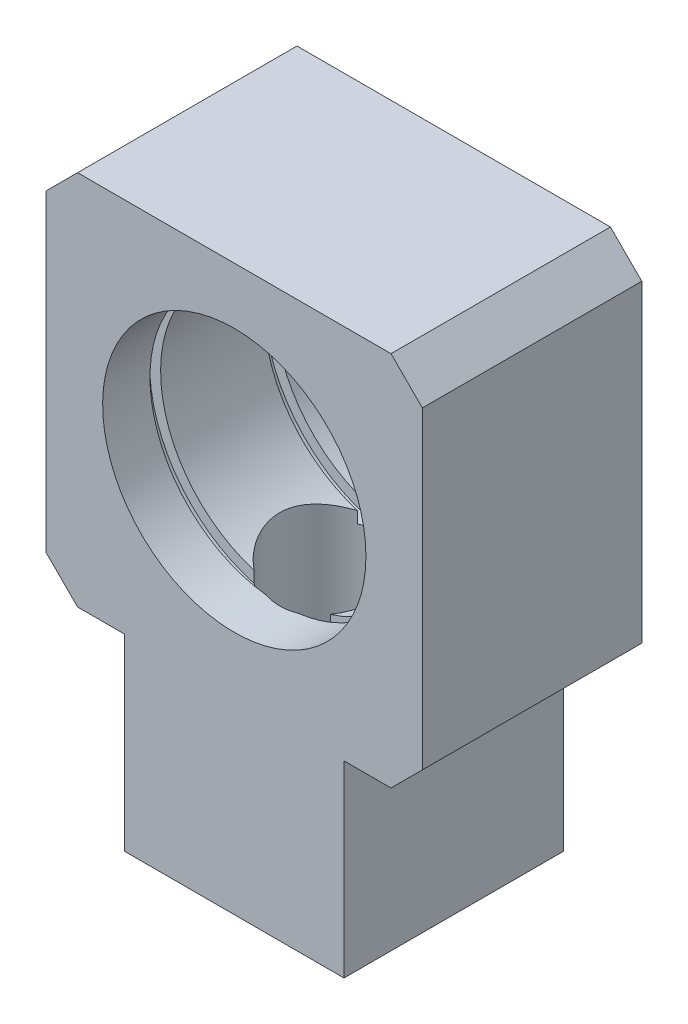
SolidWorks part; units mm, degrees
ref_plane "前视基准面" through (0, 0, 0) normal (0, 0, 1) x (1, 0, 0)
ref_plane "上视基准面" through (0, 0, 0) normal (0, 1, 0) x (1, 0, 0)
ref_plane "右视基准面" through (0, 0, 0) normal (1, 0, 0) x (0, 0, -1)
sketch "草图1" plane through (0, 0, 0) normal (0, 0, 1) x (1, 0, 0)
  line L0 (-87.1056, 0) -> (87.1056, 0) construction
  line L1 (0, 87.1056) -> (0, -87.1056) construction
  line L2 (-17.5, -24.367) -> (-17.5, -60)
  line L3 (17.5, -24.367) -> (17.5, -60)
  line L4 (-17.5, -60) -> (17.5, -60)
  line L6 (-30, -30) -> (30, -30)
  line L7 (-30, -30) -> (-30, 30)
  line L8 (-30, 30) -> (30, 30)
  line L9 (30, -30) -> (30, 30)
  line L10 (-30, -30) -> (30, 30) construction
  line L11 (-30, 30) -> (30, -30) construction
  circle A0 centre (0, 0) radius 21
  circle A1 centre (0, 0) radius 30
  dimension "D1" = 42
  dimension "D2" = 60
  dimension "D4" = 60
  dimension "D3" = 35
extrude "凸台-拉伸1" add sketch "草图1" along normal mid plane 35 contours A1 L9 L8 | A1 L8 L7 | A1 A0 | A1 L3 L6 L9 | A1 L6 L3 | A1 L2 L6 | A1 L7 L6 L2 | L6 L2 L4 L3
hole_wizard "M22x1.5 螺纹孔1" positions "草图4" profile "草图3" tap size "M22x1.5" standard "GB"
sketch "草图4" plane through (0, -60, 0) normal (0, -1, 0) x (1, 0, 0)
  point P0 (0, 0)
sketch "草图3" plane through (0, -60, 0) normal (1, 0, 0) x (0, 0, -1)
  line L0 (0, 0) -> (0, 54.6588)
  line L1 (0, 54.6588) -> (10.25, 48.5)
  line L2 (10.25, 48.5) -> (10.25, 0)
  line L5 (10.25, 0) -> (0, 0)
  line L10 (0, 54.6588) -> (-10.25, 48.5) construction
  line L11 (0, -6.35) -> (0, 107.95) construction
  dimension "螺纹孔钻头直径" = 20.5
  dimension "螺纹孔钻头深度" = 48.5
  dimension "导头角度" = 118
cosmetic thread "孔螺蚊线1" parameters "D1"=41.6714, "D2"=22
sketch "草图5" plane through (0, 0, 0) normal (0, 0, 1) x (1, 0, 0)
  circle A0 centre (0, 0) radius 22.75
  circle A1 centre (0, 0) radius 21
  circle A2 centre (0, 0) radius 21 construction
  dimension "D1" = 45.5
extrude "切除-拉伸1" cut sketch "草图5" along normal blind 1.7 from offset 8.25
mirror "镜向1" about plane through (0, 0, 0) normal (0, 0, 1) of "切除-拉伸1"
chamfer "倒角1" distance 5 distance2 5 4 edges at (30, -30, 0) (-30, -30, 0) (-30, 30, 0) (30, 30, 0)
